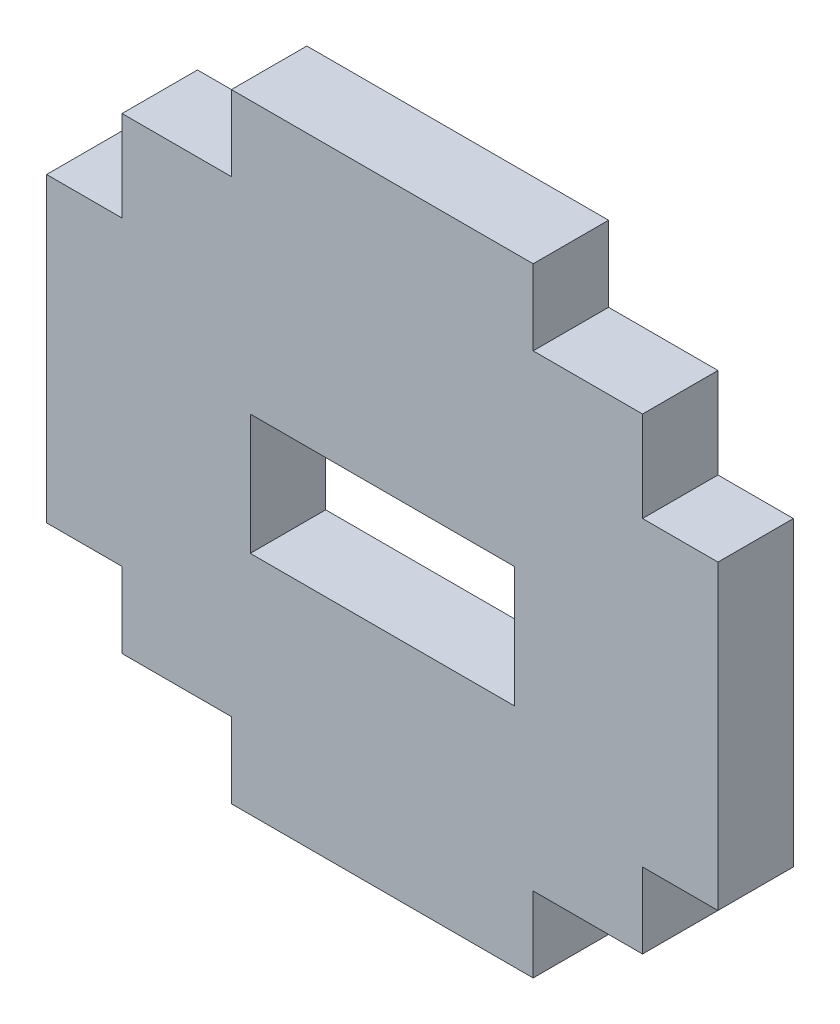
SolidWorks part; units mm, degrees
ref_plane "Front Plane" through (0, 0, 0) normal (0, 0, 1) x (1, 0, 0)
ref_plane "Top Plane" through (0, 0, 0) normal (0, 1, 0) x (1, 0, 0)
ref_plane "Right Plane" through (0, 0, 0) normal (1, 0, 0) x (0, 0, -1)
sketch "Sketch1" plane through (0, 0, 0) normal (0, 0, 1) x (1, 0, 0)
  line L1 (0, 0) -> (34.5, 0)
  line L2 (0, 0) -> (0, 31)
  line L3 (0, 31) -> (34.5, 31)
  line L4 (34.5, 0) -> (34.5, 31)
  line L5 (34.5, 25) -> (39.5, 25)
  line L6 (34.5, 25) -> (34.5, 5)
  line L7 (34.5, 5) -> (39.5, 5)
  line L8 (39.5, 25) -> (39.5, 5)
  line L9 (0, 25) -> (-5, 25)
  line L10 (0, 25) -> (0, 5)
  line L11 (0, 5) -> (-5, 5)
  line L12 (-5, 25) -> (-5, 5)
  line L13 (7.25, 0) -> (27.25, 0)
  line L14 (7.25, 0) -> (7.25, -5)
  line L15 (7.25, -5) -> (27.25, -5)
  line L16 (27.25, 0) -> (27.25, -5)
  line L17 (7.25, 31) -> (27.25, 31)
  line L18 (7.25, 31) -> (7.25, 26)
  line L19 (7.25, 26) -> (27.25, 26)
  line L20 (27.25, 31) -> (27.25, 26)
  line L21 (7.25, 31) -> (27.25, 31)
  line L22 (7.25, 31) -> (7.25, 36)
  line L23 (7.25, 36) -> (27.25, 36)
  line L24 (27.25, 31) -> (27.25, 36)
  line L25 (8.5, 18) -> (26, 18)
  line L26 (8.5, 18) -> (8.5, 10)
  line L27 (8.5, 10) -> (26, 10)
  line L28 (26, 18) -> (26, 10)
  dimension "D1" = 34.5
  dimension "D2" = 31
  dimension "D3" = 20
  dimension "D4" = 5
  dimension "D5" = 5
  dimension "D6" = 5
  dimension "D7" = 5
  dimension "D8" = 20
  dimension "D9" = 5
  dimension "D10" = 20
  dimension "D11" = 7.25
  dimension "D12" = 5
  dimension "D13" = 20
  dimension "D14" = 7.25
  dimension "D15" = 5
  dimension "D16" = 17.5
  dimension "D17" = 8.5
  dimension "D18" = 8
  dimension "D19" = 10
extrude "Boss-Extrude1" add sketch "Sketch1" along normal blind 5
